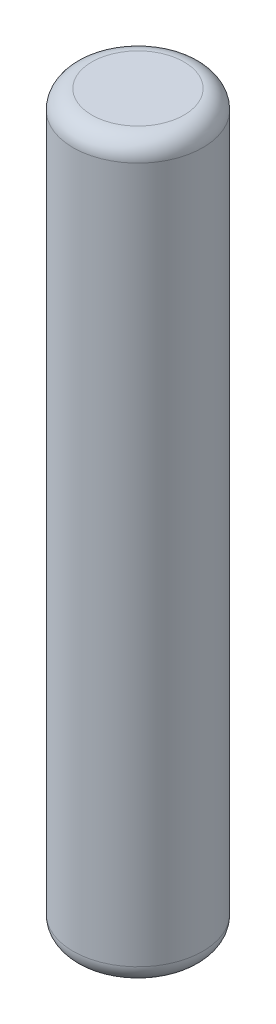
SolidWorks part; units mm, degrees
ref_plane "Front Plane" through (0, 0, 0) normal (0, 0, 1) x (1, 0, 0)
ref_plane "Top Plane" through (0, 0, 0) normal (0, 1, 0) x (1, 0, 0)
ref_plane "Right Plane" through (0, 0, 0) normal (1, 0, 0) x (0, 0, -1)
sketch "Sketch1" plane through (0, 0, 0) normal (0, 1, 0) x (1, 0, 0)
  circle A0 centre (0, 0) radius 3.45
  dimension "D1" = 6.9
extrude "Boss-Extrude1" add sketch "Sketch1" along normal mid plane 39
fillet "Fillet1" radius 1 2 edges at (0, -19.5, 3.45) (0, 19.5, 3.45)
